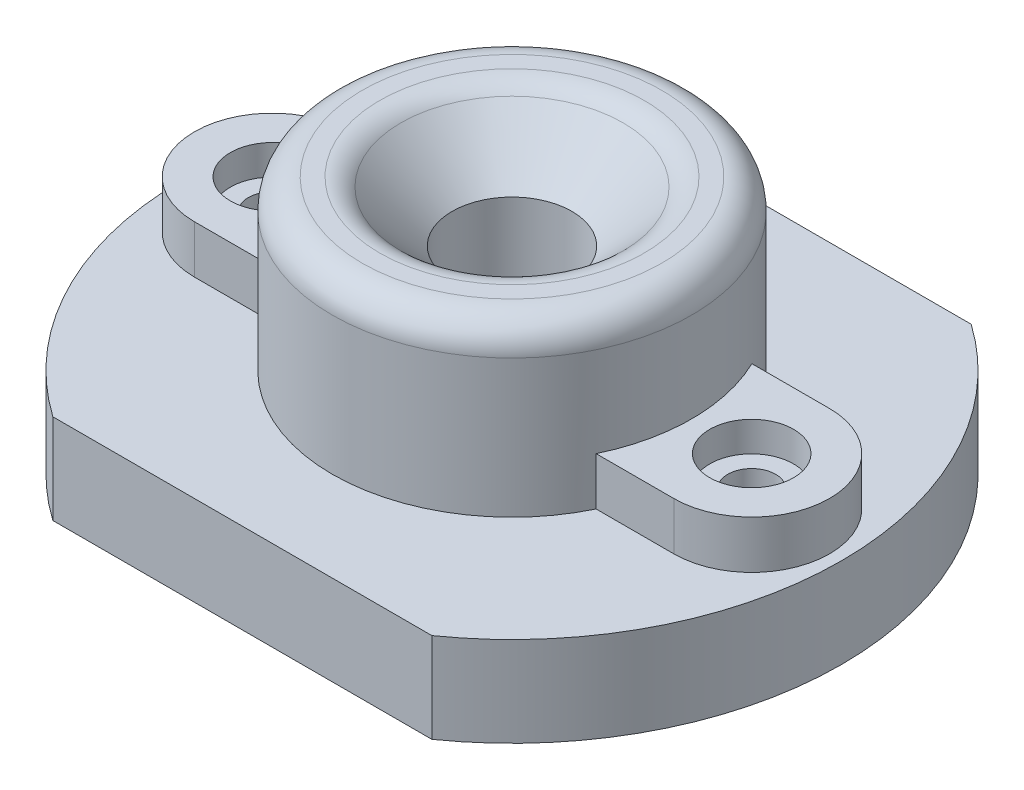
SolidWorks part; units mm, degrees
ref_plane "前视基准面" through (0, 0, 0) normal (0, 0, 1) x (1, 0, 0)
ref_plane "上视基准面" through (0, 0, 0) normal (0, 1, 0) x (1, 0, 0)
ref_plane "右视基准面" through (0, 0, 0) normal (1, 0, 0) x (0, 0, -1)
other "Configuration Table"
sketch "草图1" plane through (0, 0, 0) normal (0, 1, 0) x (1, 0, 0)
  line L0 (-31.6228, 45) -> (31.6228, 45)
  line L1 (-31.6228, -45) -> (31.6228, -45)
  arc A0 (-31.6228, 45) -> (-31.6228, -45) centre (0, 0) ccw
  arc A1 (31.6228, -45) -> (31.6228, 45) centre (0, 0) ccw
  dimension "D1" = 45
  dimension "D2" = 45
extrude "凸台-拉伸1" add sketch "草图1" along normal blind 15
sketch "草图7" plane through (0, 15, 0) normal (0, 1, 0) x (1, 0, 0)
ref_plane "基准面1" through (0, 0, 0) normal (0, 0, 1) x (1, 0, 0)
sketch "草图9" plane through (0, 0, 0) normal (0, 0, 1) x (1, 0, 0)
  line L0 (-10, 0) -> (10, 0)
  line L1 (20, 33) -> (20, 0)
  line L2 (-31.6228, 0) -> (31.6228, 0) construction
  line L3 (10, 0) -> (10, 33)
  line L4 (10, 33) -> (20, 33)
  line L5 (20, 33) -> (20, 43)
  line L6 (20, 43) -> (10, 33)
  line L7 (20, 0) -> (10, 0)
  line L8 (0, 0) -> (0, 62.6252) construction
  point P3 (0, 15)
  point P8 (0, 0)
  dimension "D1" = 20
  dimension "D2" = 33
  dimension "D3" = 10
  dimension "D4" = 10
revolve "旋转1" add sketch "草图9" angle 360 about L8
sketch "草图12" plane through (0, 0, 0) normal (0, 0, 1) x (1, 0, 0)
  line L0 (0, 0) -> (0, 43) construction
  line L1 (20, 43) -> (-20, 43) construction
  line L2 (20, 43) -> (30, 43)
  line L3 (30, 43) -> (30, 15)
  line L4 (-31.6228, 15) -> (31.6228, 15) construction
  line L5 (30, 15) -> (20, 15)
  line L6 (20, 15) -> (20, 43)
  line L7 (20, 15) -> (20, 43) construction
  dimension "D1" = 30
revolve "旋转2" add sketch "草图12" angle 360 about L0
fillet "圆角1" radius 5 2 edges at (0, 43, -30) (0, 43, -20)
sketch "草图14" plane through (0, 15, 0) normal (0, 1, 0) x (1, 0, 0)
  line L0 (0, 0) -> (-27, 0)
  line L1 (-8.25, 0) -> (8.25, 0) construction
  line L2 (-40, 13) -> (-27.037, 13)
  line L3 (-40, -13) -> (-27.037, -13)
  line L4 (0, 0) -> (0, 49.137) construction
  line L5 (40, -13) -> (27.037, -13)
  line L6 (40, 13) -> (27.037, 13)
  line L7 (-30, 0) -> (-40, 0)
  arc A0 (-40, 13) -> (-40, -13) centre (-40, 0) ccw
  circle A1 centre (0, 0) radius 30 construction
  arc A2 (40, 13) -> (40, -13) centre (40, 0) cw
  arc A3 (-27.037, 13) -> (-27.037, -13) centre (0, 0) ccw
  arc A4 (27.037, -13) -> (27.037, 13) centre (0, 0) ccw
  dimension "D1" = 26
extrude "凸台-拉伸4" add sketch "草图14" along normal blind 8
sketch "草图17" plane through (0, 23, 0) normal (0, 1, 0) x (1, 0, 0)
  line L0 (40, 13) -> (27.037, 13) construction
  line L1 (27.037, -13) -> (40, -13) construction
  line L2 (-27.037, 13) -> (-40, 13) construction
  line L3 (-40, -13) -> (-27.037, -13) construction
  line L4 (40, 13) -> (27.037, 13)
  line L5 (27.037, -13) -> (40, -13)
  line L6 (-27.037, 13) -> (-40, 13)
  line L7 (-40, -13) -> (-27.037, -13)
  arc A0 (40, -13) -> (40, 13) centre (40, 0) ccw construction
  arc A1 (27.037, -13) -> (27.037, 13) centre (0, 0) ccw construction
  arc A2 (-40, 13) -> (-40, -13) centre (-40, 0) ccw construction
  arc A3 (-27.037, 13) -> (-27.037, -13) centre (0, 0) ccw construction
  arc A4 (40, -13) -> (40, 13) centre (40, 0) ccw
  arc A5 (27.037, -13) -> (27.037, 13) centre (0, 0) ccw
  arc A6 (-40, 13) -> (-40, -13) centre (-40, 0) ccw
  arc A7 (-27.037, 13) -> (-27.037, -13) centre (0, 0) ccw
  circle A8 centre (-40, 0) radius 7
  circle A9 centre (40, 0) radius 7
extrude "切除-拉伸1" cut sketch "草图17" against normal blind 5 contours A8 | A9
sketch "草图18" plane through (0, 23, 0) normal (0, 1, 0) x (1, 0, 0)
  circle A0 centre (40, 0) radius 7 construction
  circle A1 centre (-40, 0) radius 7 construction
  circle A2 centre (40, 0) radius 7
  circle A3 centre (-40, 0) radius 7
  circle A4 centre (-40, 0) radius 4
  circle A5 centre (40, 0) radius 4
extrude "切除-拉伸2" cut sketch "草图18" against normal through all both and the other way through all contours A4 | A5
